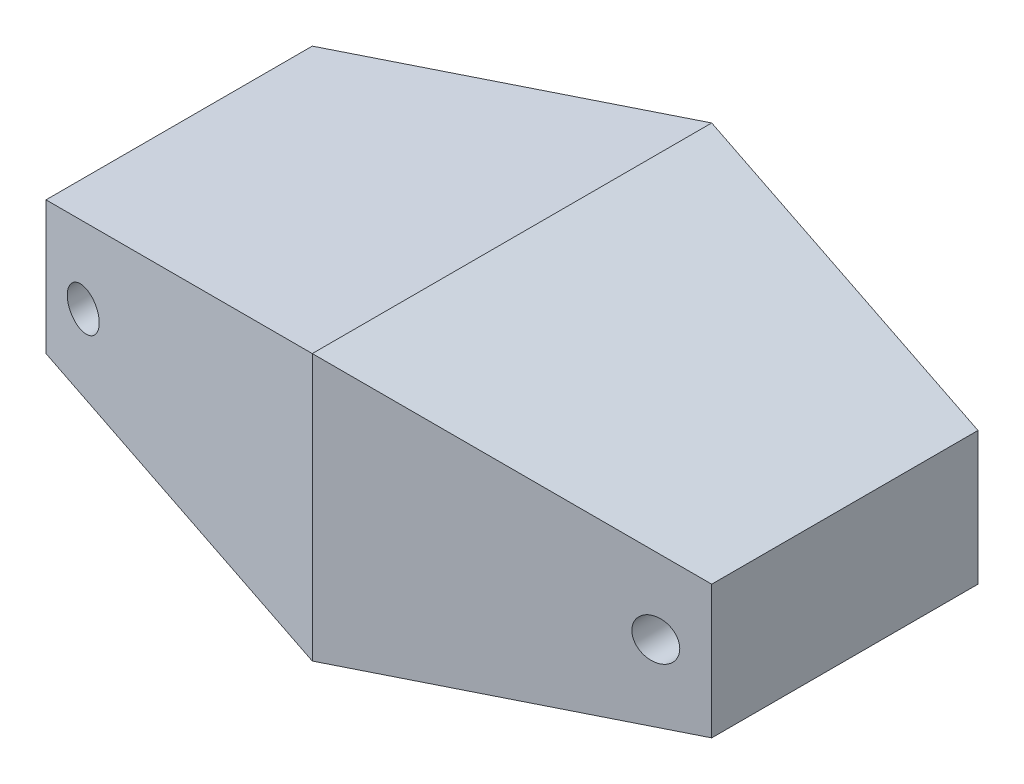
SolidWorks part; units mm, degrees
ref_plane "Front Plane" through (0, 0, 0) normal (0, 0, 1) x (1, 0, 0)
ref_plane "Top Plane" through (0, 0, 0) normal (0, 1, 0) x (1, 0, 0)
ref_plane "Right Plane" through (0, 0, 0) normal (1, 0, 0) x (0, 0, -1)
sketch "Sketch1" plane through (0, 0, 0) normal (0, 0, 1) x (1, 0, 0)
  line L1 (-50, -20) -> (50, -20)
  line L2 (-50, -20) -> (-50, 20)
  line L3 (-50, 20) -> (50, 20)
  line L4 (50, -20) -> (50, 20)
  line L5 (-50, -20) -> (50, 20) construction
  line L6 (-50, 20) -> (50, -20) construction
  point P0 (0, 0)
  dimension "D1" = 100
  dimension "D2" = 40
extrude "Boss-Extrude1" add sketch "Sketch1" along normal blind 60
sketch "Sketch2" plane through (0, 20, 0) normal (0, 1, 0) x (1, 0, 0)
  line L0 (0, 0) -> (0, -60) construction
  line L1 (50, -60) -> (-50, -60) construction
  line L2 (-54.1271, -30) -> (50.6753, -30) construction
  line L3 (-50, -60) -> (-50, 0) construction
  line L4 (-50, -50) -> (0, -60)
  line L5 (-50, -50) -> (-50, -60)
  line L6 (-50, -60) -> (0, -60)
  line L7 (50, -50) -> (0, -60)
  line L8 (50, -10) -> (0, 0)
  line L9 (-50, -10) -> (0, 0)
  line L10 (-50, -10) -> (-50, 0)
  line L11 (-50, 0) -> (0, 0)
  line L12 (0, 0) -> (50, 0)
  line L13 (50, 0) -> (50, -10)
  line L14 (50, -50) -> (50, -60)
  line L15 (50, -60) -> (0, -60)
  line M10 (50, 0) -> (-50, 0)
  line M11 (-50, 0) -> (-50, -60)
  line M12 (-50, -60) -> (50, -60)
  line M13 (50, -60) -> (50, 0)
  dimension "D1" = 20
  dimension "D2" = 30
extrude "Cut-Extrude1" cut sketch "Sketch2" against normal blind 40 contours L4 M11 M12 | L7 M13 M12 | L8 M13 M10 | L9 M11 M10
sketch "Sketch4" plane through (0, 0, 0) normal (0, 0, 1) x (1, 0, 0)
  line L0 (0, 20) -> (-50, 10)
  line L1 (-50, -20) -> (-50, 20) construction
  line L2 (-50, 20) -> (0, 20) construction
  line L3 (0, 20) -> (0, -22.0056) construction
  line L4 (-50, 0) -> (52.4971, 0) construction
  line L5 (0, 20) -> (50, 10)
  line L6 (0, -20) -> (50, -10)
  line L7 (0, -20) -> (-50, -10)
  line L8 (-50, 10) -> (-50, 20)
  line L9 (-50, 20) -> (0, 20)
  line L10 (-50, 20) -> (0, 20)
  line L11 (0, 20) -> (50, 20)
  line L12 (50, 20) -> (0, 20) construction
  line L13 (50, 20) -> (50, 10)
  line L14 (50, -10) -> (50, -20)
  line L15 (50, -20) -> (0, -20)
  line L16 (-50, -10) -> (-50, -20)
  line L17 (-50, -20) -> (0, -20)
  dimension "D1" = 10
extrude "Cut-Extrude2" cut sketch "Sketch4" along normal through all contours L9 L8 L0 | L13 L11 L5 | L15 L14 L6 | L16 L17 L7
sketch "Sketch5" plane through (0, 0, 0) normal (0, 0, 1) x (1, 0, 0)
  line L0 (0, 0) -> (0, 7.2393) construction
  line L1 (0, -20) -> (0, 20) construction
  line L2 (-50, -10) -> (-50, 10) construction
  circle A0 centre (-43, 0) radius 3
  circle A1 centre (43, 0) radius 3
  dimension "D1" = 7
extrude "Cut-Extrude3" cut sketch "Sketch5" along normal through all
